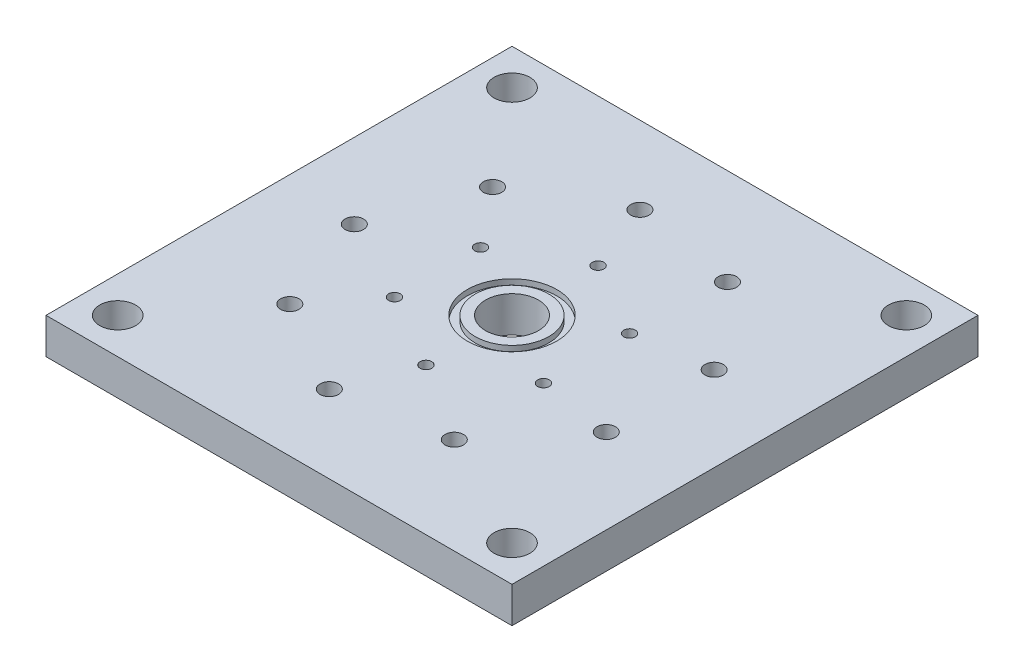
SolidWorks part; units mm, degrees
ref_plane "Front Plane" through (0, 0, 0) normal (0, 0, 1) x (1, 0, 0)
ref_plane "Top Plane" through (0, 0, 0) normal (0, 1, 0) x (1, 0, 0)
ref_plane "Right Plane" through (0, 0, 0) normal (1, 0, 0) x (0, 0, -1)
sketch "Sketch1" plane through (0, 0, 0) normal (0, 1, 0) x (1, 0, 0)
  line L1 (-41.275, -41.275) -> (41.275, -41.275)
  line L2 (-41.275, -41.275) -> (-41.275, 41.275)
  line L3 (-41.275, 41.275) -> (41.275, 41.275)
  line L4 (41.275, -41.275) -> (41.275, 41.275)
  line L5 (-41.275, -41.275) -> (41.275, 41.275) construction
  line L6 (-41.275, 41.275) -> (41.275, -41.275) construction
  point P0 (0, 0)
  dimension "D1" = 82.55
  dimension "D2" = 82.55
extrude "Boss-Extrude1" add sketch "Sketch1" along normal blind 6.35
sketch "Sketch2" plane through (0, 6.35, 0) normal (0, 1, 0) x (1, 0, 0)
  circle A0 centre (0, 0) radius 4.699
  dimension "D1" = 9.398
extrude "Cut-Extrude1" cut sketch "Sketch2" against normal up to next
sketch "Sketch4" plane through (0, 6.35, 0) normal (0, 1, 0) x (1, 0, 0)
  circle A0 centre (0, 0) radius 6.5278
  circle A1 centre (0, 0) radius 7.9248
  dimension "D1" = 1.397
extrude "Cut-Extrude3" cut sketch "Sketch4" against normal blind 0.9779
sketch "Sketch5" plane through (0, 6.35, 0) normal (0, 1, 0) x (1, 0, 0)
  circle A0 centre (0, 0) radius 15.24 construction
  circle A1 centre (0, -15.24) radius 1.0325
  dimension "D1" = 2.065
extrude "Cut-Extrude4" cut sketch "Sketch5" against normal blind 3.175
pattern_circular "CirPattern1" count 6 over 360 about axis through (0, 0, 0) along (0, 1, 0) of "Cut-Extrude4"
sketch "Sketch6" plane through (0, 6.35, 0) normal (0, 1, 0) x (1, 0, 0)
  line L0 (0, 0) -> (13.97, -24.1967) construction
  circle A0 centre (0, 0) radius 27.94 construction
  circle A1 centre (13.97, -24.1967) radius 1.632
extrude "Cut-Extrude5" cut sketch "Sketch6" against normal up to next
pattern_circular "CirPattern2" count 9 over 360 about axis through (0, 0, 0) along (0, 1, 0) of "Cut-Extrude5"
sketch "Sketch7" plane through (0, 6.35, 0) normal (0, 1, 0) x (1, 0, 0)
  line L0 (41.275, 41.275) -> (-41.275, 41.275) construction
  line L1 (41.275, -41.275) -> (41.275, 41.275) construction
  line L2 (0, 0) -> (41.275, 0) construction
  line L3 (0, 0) -> (0, 41.275) construction
  circle A0 centre (34.925, 34.925) radius 3.175
  circle A1 centre (0, 0) radius 38.1 construction
  circle A2 centre (34.925, -34.925) radius 3.175
  circle A3 centre (-34.925, -34.925) radius 3.175
  circle A4 centre (-34.925, 34.925) radius 3.175
  circle A5 centre (34.925, 34.925) radius 5.5562 construction
  dimension "D1" = 6.35
  dimension "D2" = 6.35
extrude "Cut-Extrude6" cut sketch "Sketch7" against normal up to next
equation "\"AnnulusPlateThickness\"= 0.25"
equation "\"D1@Boss-Extrude1\"=\"AnnulusPlateThickness\""
equation "\"AnnulusRadius\"= 0.185"
equation "\"D1@Sketch2\"=\"AnnulusRadius\"*2"
